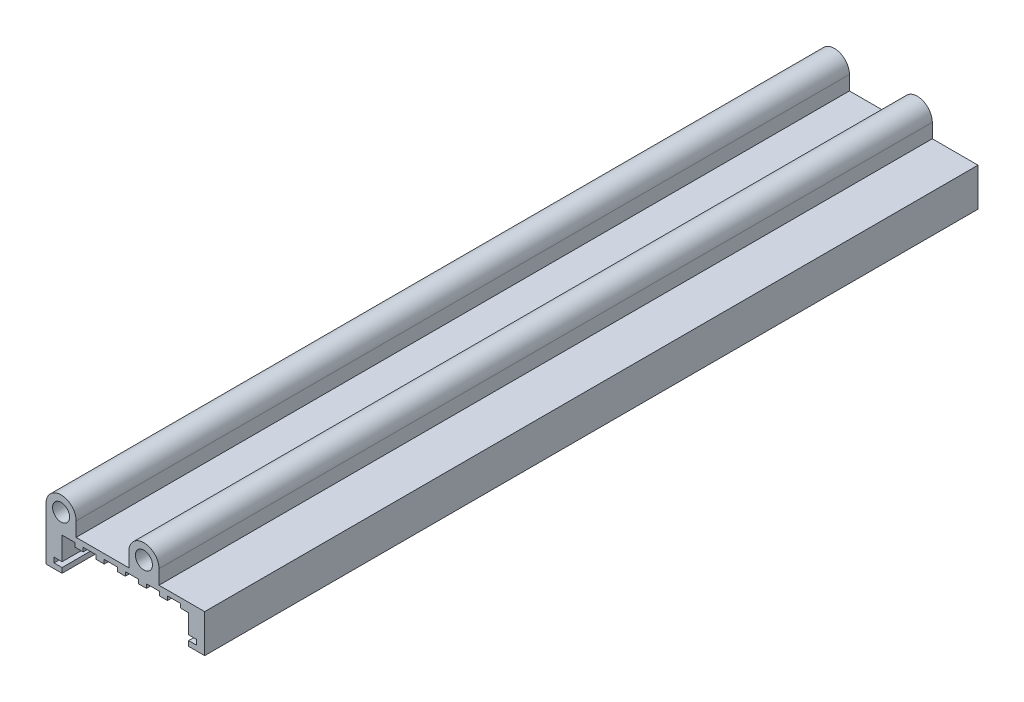
SolidWorks part; units mm, degrees
material "1023 Carbon Steel Sheet (SS)"
ref_plane "Front Plane" through (0, 0, 0) normal (0, 0, 1) x (1, 0, 0)
ref_plane "Top Plane" through (0, 0, 0) normal (0, 1, 0) x (1, 0, 0)
ref_plane "Right Plane" through (0, 0, 0) normal (1, 0, 0) x (0, 0, -1)
sketch "Sketch1" plane through (0, 0, 0) normal (0, 0, 1) x (1, 0, 0)
  line L0 (0, 0) -> (-4.064, 0)
  line L1 (-4.064, 0) -> (-4.064, 9.652)
  line L2 (0, 0) -> (0, 1.27)
  line L3 (0, 1.27) -> (-2.032, 1.27)
  line L4 (-2.032, 1.27) -> (-2.032, 2.54)
  line L5 (-2.032, 2.54) -> (0, 2.54)
  line L6 (0, 2.54) -> (0, 8.382)
  line L7 (0, 8.382) -> (3.302, 8.382)
  line L8 (3.302, 8.382) -> (3.302, 7.366)
  line L9 (3.302, 7.366) -> (5.334, 7.366)
  line L10 (5.334, 7.366) -> (5.334, 8.382)
  line L11 (5.334, 8.382) -> (8.636, 8.382)
  line L12 (8.636, 8.382) -> (8.636, 7.366)
  line L13 (8.636, 7.366) -> (10.668, 7.366)
  line L14 (10.668, 7.366) -> (10.668, 8.382)
  line L15 (10.668, 8.382) -> (13.97, 8.382)
  line L16 (13.97, 8.382) -> (13.97, 7.366)
  line L17 (13.97, 7.366) -> (16.002, 7.366)
  line L18 (16.002, 7.366) -> (16.002, 8.382)
  line L19 (16.002, 8.382) -> (19.304, 8.382)
  line L20 (19.304, 8.382) -> (19.304, 7.366)
  line L21 (19.304, 7.366) -> (21.336, 7.366)
  line L22 (21.336, 7.366) -> (21.336, 8.382)
  line L23 (21.336, 8.382) -> (24.638, 8.382)
  line L24 (24.638, 8.382) -> (24.638, 7.366)
  line L25 (24.638, 7.366) -> (26.67, 7.366)
  line L26 (26.67, 7.366) -> (26.67, 8.382)
  line L27 (26.67, 8.382) -> (29.972, 8.382)
  line L28 (29.972, 8.382) -> (29.972, 7.366)
  line L29 (29.972, 7.366) -> (32.004, 7.366)
  line L30 (34.036, 1.27) -> (34.036, 2.54)
  line L31 (34.036, 2.54) -> (32.004, 2.54)
  line L32 (32.004, 2.54) -> (32.004, 7.366)
  line L33 (34.036, 1.27) -> (32.004, 1.27)
  line L34 (32.004, 1.27) -> (32.004, 0)
  line L35 (32.004, 0) -> (36.068, 0)
  line L36 (36.068, 0) -> (36.068, 9.652)
  line L37 (3.556, 9.652) -> (16.891, 9.652)
  line L38 (-0.254, 13.2588) -> (20.701, 13.2588) construction
  line L39 (3.556, 13.2588) -> (3.556, 9.652)
  line L40 (-4.064, 9.652) -> (-4.064, 13.2588)
  line L41 (16.891, 13.2588) -> (16.891, 9.652)
  line L42 (24.511, 13.2588) -> (24.511, 9.652)
  line L43 (24.511, 9.652) -> (36.068, 9.652)
  circle A0 centre (-0.254, 13.2588) radius 2.159
  arc A1 (-4.064, 13.2588) -> (3.556, 13.2588) centre (-0.254, 13.2588) cw
  circle A2 centre (20.701, 13.2588) radius 2.159
  arc A4 (24.511, 13.2588) -> (16.891, 13.2588) centre (20.701, 13.2588) ccw
  dimension "D2" = 1.27
  dimension "D3" = 5.8928
  dimension "D4" = 9.652
  dimension "D15" = 20.955
  dimension "D13" = 3.81
  dimension "D14" = 4.318
  dimension "D18" = 7.62
  dimension "D5" = 1.27
  dimension "D6" = 2.032
  dimension "D7" = 4.064
  dimension "D8" = 4.064
  dimension "D9" = 1.27
  dimension "D10" = 2.032
  dimension "D11" = 3.302
  dimension "D12" = 2.032
  dimension "D17" = 1.016
  dimension "D19" = 9.652
extrude "Boss-Extrude1" add sketch "Sketch1" against normal blind 195.58
sketch "Sketch2" plane through (-4.064, 0, 0) normal (-1, 0, 0) x (0, 0, 1)
  line L0 (0, 6.6294) -> (-88.1216, 6.6294) construction
  line L1 (0, 13.2588) -> (0, 0) construction
  circle A0 centre (-33.02, 6.6294) radius 1.5875
  circle A1 centre (-50.8, 6.6294) radius 1.5875
  dimension "D2" = 50.8
  dimension "D3" = 3.175
  dimension "D1" = 33.02
extrude "Cut-Extrude1" cut sketch "Sketch2" against normal blind 2.54
